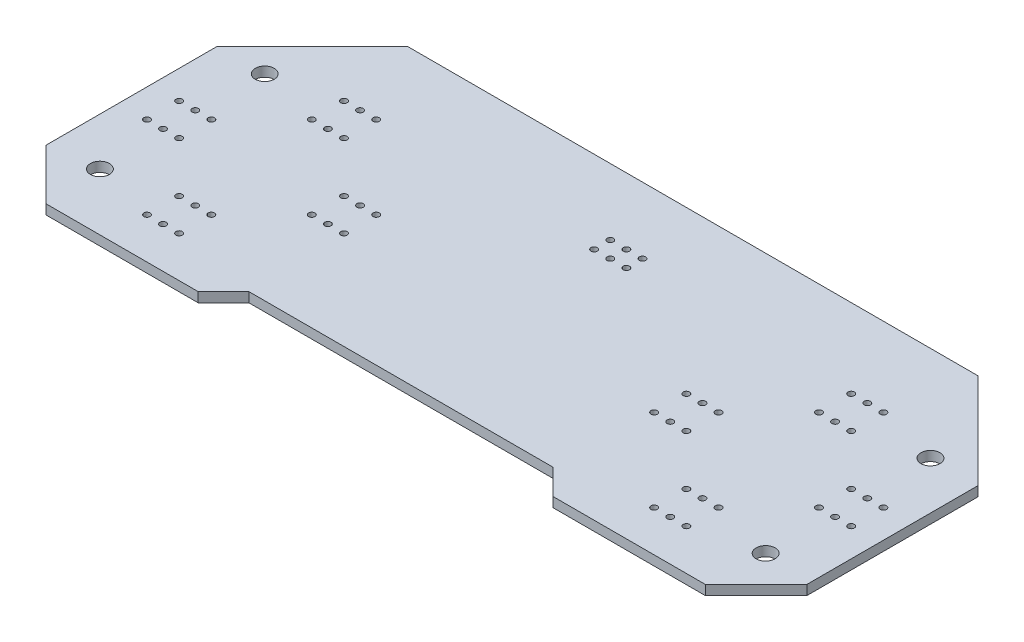
SolidWorks part; units mm, degrees
ref_plane "Front Plane" through (0, 0, 0) normal (0, 0, 1) x (1, 0, 0)
ref_plane "Top Plane" through (0, 0, 0) normal (0, 1, 0) x (1, 0, 0)
ref_plane "Right Plane" through (0, 0, 0) normal (1, 0, 0) x (0, 0, -1)
sketch "Sketch1" plane through (0, 0, 0) normal (0, 1, 0) x (1, 0, 0)
  line L0 (0, 0) -> (0, 13) construction
  line L1 (-60, -22) -> (60, -22)
  line L2 (-60, -22) -> (-60, 28)
  line L3 (-60, 28) -> (60, 28)
  line L4 (60, -22) -> (60, 28)
  line L5 (0, 0) -> (60, 28) construction
  line L6 (-60, 28) -> (0, 0) construction
  line L7 (-52.5, 13) -> (52.5, 13) construction
  line L8 (-52.5, 13) -> (-52.5, -13) construction
  line L9 (-52.5, -13) -> (52.5, -13) construction
  line L10 (52.5, 13) -> (52.5, -13) construction
  line L11 (0, 13) -> (0, 28) construction
  line L12 (-52.5, 13) -> (0, 0) construction
  line L13 (0, 0) -> (52.5, -13) construction
  circle A0 centre (52.5, 13) radius 1.5
  circle A1 centre (52.5, -13) radius 1.5
  circle A2 centre (-52.5, -13) radius 1.5
  circle A3 centre (-52.5, 13) radius 1.5
  point P0 (0, 0)
  point P6 (-55, 13.3729)
  dimension "D4" = 3
  dimension "D1" = 120
  dimension "D2" = 28
  dimension "D3" = 26
  dimension "D5" = 105
  dimension "D6" = 22
extrude "Boss-Extrude1" add sketch "Sketch1" along normal blind 1.53
sketch "Sketch2" plane through (0, 1.53, 0) normal (0, 1, 0) x (1, 0, 0)
  line L0 (-55.54, 2.54) -> (-53, 2.54) construction
  line L1 (-53, 2.54) -> (-50.46, 2.54) construction
  line L2 (-53, 2.54) -> (-53, -2.54) construction
  line L3 (-53, -2.54) -> (-50.46, -2.54) construction
  line L4 (-53, -2.54) -> (-55.54, -2.54) construction
  line L5 (-53, 0) -> (-27, 0) construction
  line L6 (-29.54, 2.54) -> (-27, 2.54) construction
  line L7 (-27, 2.54) -> (-24.46, 2.54) construction
  line L8 (-27, 2.54) -> (-27, -2.54) construction
  line L9 (-27, -2.54) -> (-24.46, -2.54) construction
  line L10 (-27, -2.54) -> (-29.54, -2.54) construction
  line L11 (-42.54, 15.54) -> (-40, 15.54) construction
  line L12 (-40, 15.54) -> (-37.46, 15.54) construction
  line L13 (-40, 15.54) -> (-40, 10.46) construction
  line L14 (-40, 10.46) -> (-37.46, 10.46) construction
  line L15 (-40, 10.46) -> (-42.54, 10.46) construction
  line L16 (-42.54, -10.46) -> (-40, -10.46) construction
  line L17 (-40, -10.46) -> (-37.46, -10.46) construction
  line L18 (-40, -10.46) -> (-40, -15.54) construction
  line L19 (-40, -15.54) -> (-37.46, -15.54) construction
  line L20 (-40, -15.54) -> (-42.54, -15.54) construction
  line L21 (-40, -13) -> (-40, 0) construction
  line L22 (-40, 0) -> (-40, 13) construction
  line L23 (-27, 0) -> (0, 0) construction
  circle A0 centre (-55.54, 2.54) radius 0.5
  circle A1 centre (-53, 2.54) radius 0.5
  circle A2 centre (-50.46, 2.54) radius 0.5
  circle A3 centre (-55.54, -2.54) radius 0.5
  circle A4 centre (-53, -2.54) radius 0.5
  circle A5 centre (-50.46, -2.54) radius 0.5
  circle A6 centre (-29.54, 2.54) radius 0.5
  circle A7 centre (-27, 2.54) radius 0.5
  circle A8 centre (-24.46, 2.54) radius 0.5
  circle A9 centre (-29.54, -2.54) radius 0.5
  circle A10 centre (-27, -2.54) radius 0.5
  circle A11 centre (-24.46, -2.54) radius 0.5
  circle A12 centre (-42.54, 15.54) radius 0.5
  circle A13 centre (-40, 15.54) radius 0.5
  circle A14 centre (-37.46, 15.54) radius 0.5
  circle A15 centre (-42.54, 10.46) radius 0.5
  circle A16 centre (-40, 10.46) radius 0.5
  circle A17 centre (-37.46, 10.46) radius 0.5
  circle A18 centre (-42.54, -10.46) radius 0.5
  circle A19 centre (-40, -10.46) radius 0.5
  circle A20 centre (-37.46, -10.46) radius 0.5
  circle A21 centre (-42.54, -15.54) radius 0.5
  circle A22 centre (-40, -15.54) radius 0.5
  circle A23 centre (-37.46, -15.54) radius 0.5
  point P15 (-27, 0)
  dimension "D1" = 1
  dimension "D2" = 2.54
  dimension "D3" = 5.08
  dimension "D4" = 26
  dimension "D5" = 26
  dimension "D6" = 40
extrude "Cut-Extrude1" cut sketch "Sketch2" against normal through all
mirror "Mirror1" about plane through (0, 0, 0) normal (1, 0, 0) of "Cut-Extrude1"
sketch "Sketch5" plane through (0, 1.53, 0) normal (0, 1, 0) x (1, 0, 0)
  line L0 (-2.54, 17.54) -> (0, 17.54) construction
  line L1 (0, 17.54) -> (2.54, 17.54) construction
  line L2 (0, 17.54) -> (0, 15) construction
  line L3 (0, 15) -> (2.54, 15) construction
  line L4 (0, 15) -> (-2.54, 15) construction
  line L5 (0, 0) -> (0, 15) construction
  circle A0 centre (-2.54, 17.54) radius 0.5
  circle A1 centre (0, 17.54) radius 0.5
  circle A2 centre (2.54, 17.54) radius 0.5
  circle A3 centre (-2.54, 15) radius 0.5
  circle A4 centre (0, 15) radius 0.5
  circle A5 centre (2.54, 15) radius 0.5
  dimension "D1" = 2.54
  dimension "D2" = 2.54
  dimension "D3" = 15
extrude "Cut-Extrude2" cut sketch "Sketch5" against normal through all
sketch "Sketch6" plane through (0, 1.53, 0) normal (0, 1, 0) x (1, 0, 0)
  line L0 (-45, 28) -> (-60, 13)
  line L1 (60, 28) -> (-60, 28) construction
  line L2 (-60, 28) -> (-60, -22) construction
  line L3 (-60, 13) -> (-60, -14)
  line L4 (-60, -14) -> (-52, -22)
  line L5 (-60, -22) -> (60, -22) construction
  line L6 (-52, -22) -> (-28, -22)
  line L7 (-28, -22) -> (-24, -18)
  line L8 (-24, -18) -> (24, -18)
  line L9 (24, -18) -> (28, -22)
  line L10 (28, -22) -> (52, -22)
  line L11 (52, -22) -> (60, -14)
  line L12 (60, -22) -> (60, 28) construction
  line L13 (60, -14) -> (60, 13)
  line L14 (60, 13) -> (45, 28)
  line L15 (45, 28) -> (-45, 28)
  line L16 (0, 0) -> (0, -18) construction
  line L17 (0, 0) -> (0, 28) construction
  line L19 (-70.5255, -34.7658) -> (70.5255, -34.7658)
  line L20 (-70.5255, -34.7658) -> (-70.5255, 34.7658)
  line L21 (-70.5255, 34.7658) -> (70.5255, 34.7658)
  line L22 (70.5255, -34.7658) -> (70.5255, 34.7658)
  line L23 (-70.5255, -34.7658) -> (70.5255, 34.7658) construction
  line L24 (-70.5255, 34.7658) -> (70.5255, -34.7658) construction
  dimension "D1" = 45
  dimension "D2" = 45
  dimension "D3" = 90
  dimension "D4" = 14
  dimension "D5" = 18
  dimension "D6" = 24
extrude "Cut-Extrude4" cut sketch "Sketch6" against normal through all contours L20 L21 L22 L19
